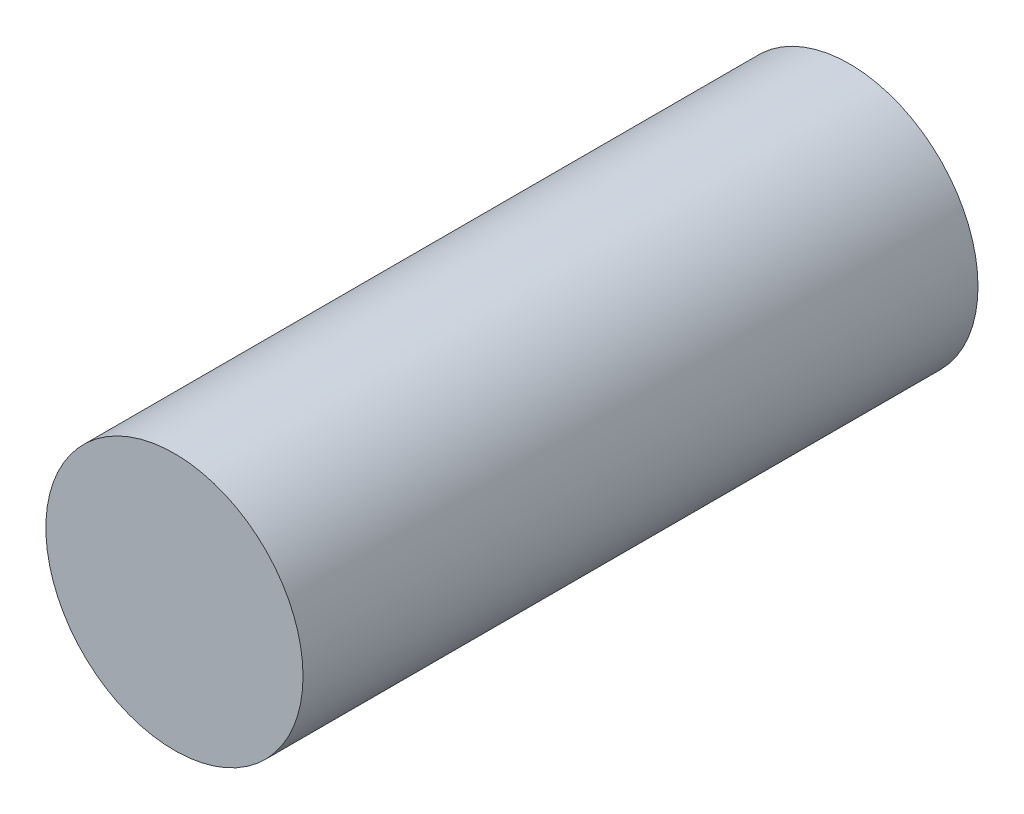
SolidWorks part; units mm, degrees
ref_plane "Front Plane" through (0, 0, 0) normal (0, 0, 1) x (1, 0, 0)
ref_plane "Top Plane" through (0, 0, 0) normal (0, 1, 0) x (1, 0, 0)
ref_plane "Right Plane" through (0, 0, 0) normal (1, 0, 0) x (0, 0, -1)
sketch "Sketch1" plane through (0, 0, 0) normal (0, 0, 1) x (1, 0, 0)
  circle A0 centre (0, 0) radius 9.525
  dimension "D1" = 19.05
extrude "Boss-Extrude1" add sketch "Sketch1" along normal blind 50
